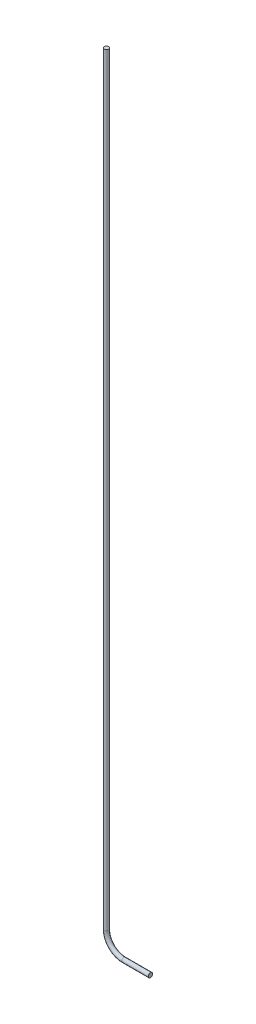
SolidWorks part; units mm, degrees
ref_plane "Front Plane" through (0, 0, 0) normal (0, 0, 1) x (1, 0, 0)
ref_plane "Top Plane" through (0, 0, 0) normal (0, 1, 0) x (1, 0, 0)
ref_plane "Right Plane" through (0, 0, 0) normal (1, 0, 0) x (0, 0, -1)
sketch "Sketch1" plane through (0, 0, 0) normal (0, 0, 1) x (1, 0, 0)
  line L0 (0, 50.8) -> (0, 2253.996)
  line L1 (50.8, 0) -> (127, 0)
  arc A0 (0, 50.8) -> (50.8, 0) centre (50.8, 50.8) ccw
  point P6 (0, 0)
  dimension "D2" = 50.8
  dimension "D1" = 127
  dimension "Length from Tank Model" = 2253.996
sweep "Sweep1" add path "Sketch1" circular profile diameter 12.7 parameters "D3"=12.7
equation "\"rebar diameter\"= .5"
equation "\"D3@Sweep1\"=\"rebar diameter\""
